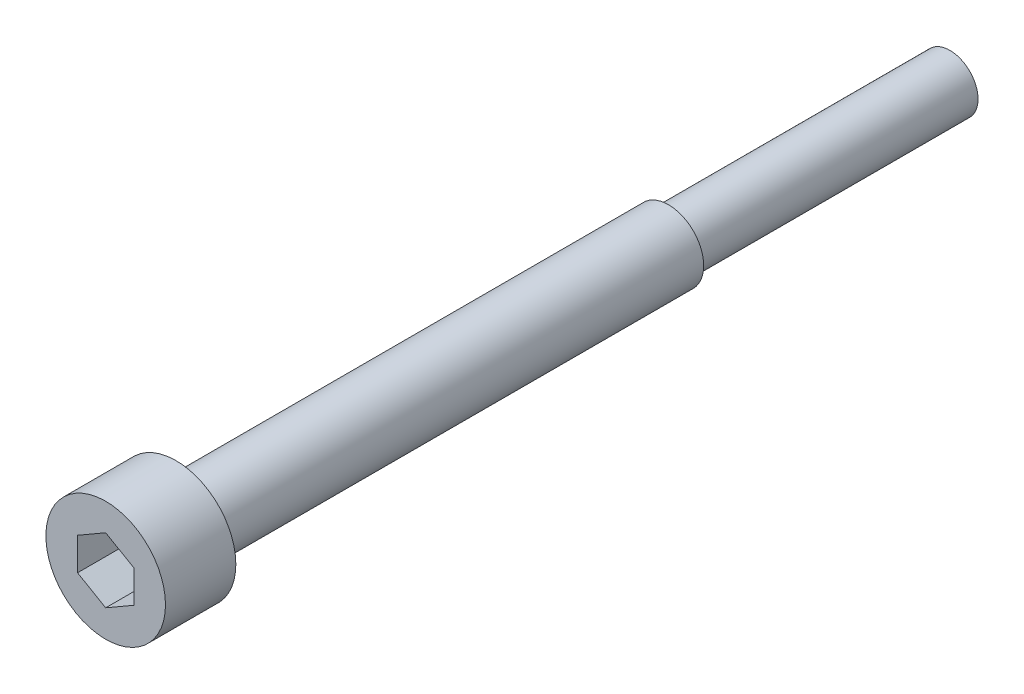
SolidWorks part; units mm, degrees
material "炭素鋼(普通)"
ref_plane "正面" through (0, 0, 0) normal (0, 0, 1) x (1, 0, 0)
ref_plane "平面" through (0, 0, 0) normal (0, 1, 0) x (1, 0, 0)
ref_plane "右側面" through (0, 0, 0) normal (1, 0, 0) x (0, 0, -1)
sketch "ｽｹｯﾁ1" plane through (0, 0, 0) normal (0, 0, 1) x (1, 0, 0)
  circle A0 centre (0, 0) radius 2.5
  dimension "D1" = 5
extrude "ﾎﾞｽ - 押し出し1" add sketch "ｽｹｯﾁ1" along normal blind 55
sketch "ｽｹｯﾁ2" plane through (0, 0, 55) normal (0, 0, 1) x (1, 0, 0)
  circle A0 centre (0, 0) radius 4.25
  dimension "D1" = 8.5
extrude "ﾎﾞｽ - 押し出し2" add sketch "ｽｹｯﾁ2" along normal blind 5
sketch "ｽｹｯﾁ3" plane through (0, 0, 60) normal (0, 0, 1) x (1, 0, 0)
  line L1 (0, 2.3094) -> (-2, 1.1547)
  line L2 (-2, 1.1547) -> (-2, -1.1547)
  line L3 (-2, -1.1547) -> (0, -2.3094)
  line L4 (0, -2.3094) -> (2, -1.1547)
  line L5 (2, -1.1547) -> (2, 1.1547)
  line L6 (2, 1.1547) -> (0, 2.3094)
  circle A0 centre (0, 0) radius 2 construction
  dimension "D1" = 4
extrude "ｶｯﾄ - 押し出し1" cut sketch "ｽｹｯﾁ3" against normal blind 3
sketch "ｽｹｯﾁ4" plane through (0, 0, 0) normal (0, 0, -1) x (-1, 0, 0)
  circle A1 centre (0, 0) radius 2
  circle A2 centre (0, 0) radius 2.5
  circle A3 centre (0, 0) radius 2.5 construction
  dimension "D1" = 4
extrude "ｶｯﾄ - 押し出し2" cut sketch "ｽｹｯﾁ4" against normal blind 20
